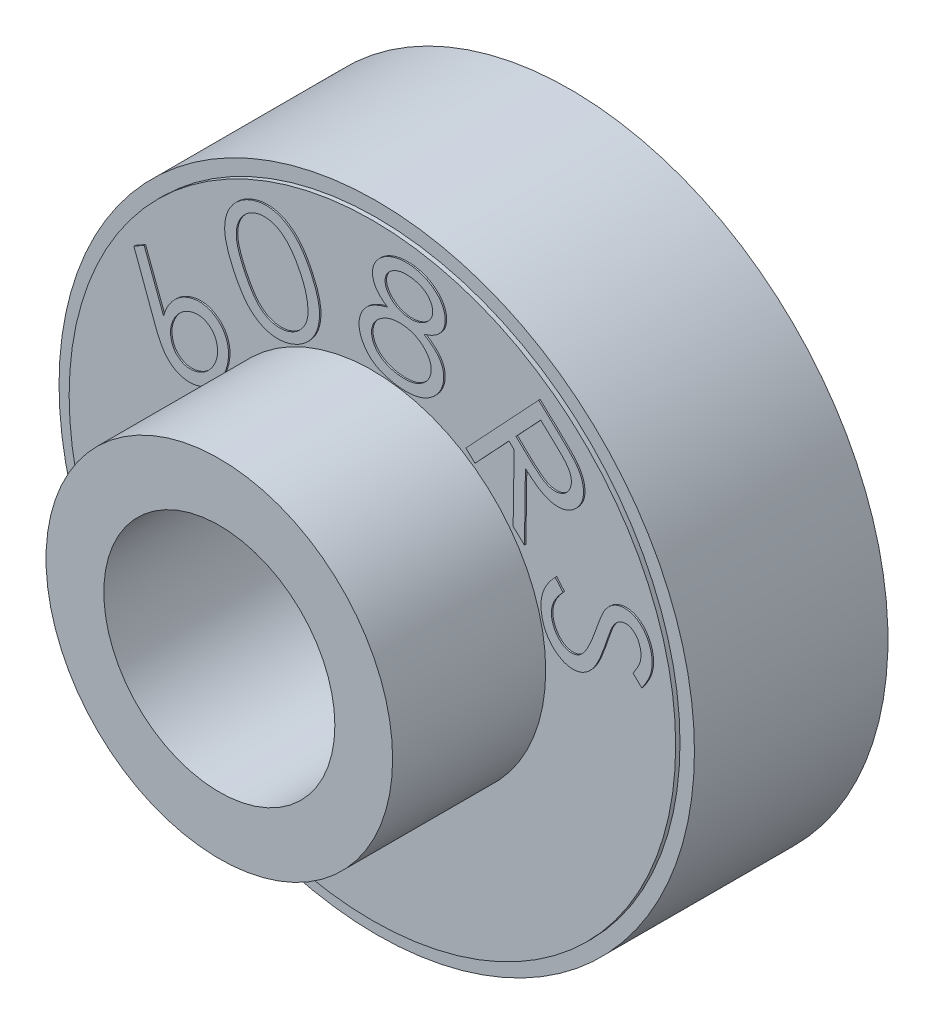
SolidWorks part; units mm, degrees
ref_plane "Front Plane" through (0, 0, 0) normal (0, 0, 1) x (1, 0, 0)
ref_plane "Top Plane" through (0, 0, 0) normal (0, 1, 0) x (1, 0, 0)
ref_plane "Right Plane" through (0, 0, 0) normal (1, 0, 0) x (0, 0, -1)
sketch "Sketch1" plane through (0, 0, 0) normal (0, 0, 1) x (1, 0, 0)
  circle A0 centre (0, 0) radius 11
extrude "Boss-Extrude1" add sketch "Sketch1" along normal blind 7
sketch "Sketch2" plane through (0, 0, 7) normal (0, 0, 1) x (1, 0, 0)
  circle A0 centre (0, 0) radius 4
extrude "Cut-Extrude1" cut sketch "Sketch2" against normal through all
sketch "Sketch3" plane through (0, 0, 7) normal (0, 0, 1) x (1, 0, 0)
  circle A0 centre (0, 0) radius 6
  circle A1 centre (0, 0) radius 4
extrude "Boss-Extrude2" add sketch "Sketch3" along normal blind 5.3
sketch "Sketch4" plane through (0, 0, 7) normal (0, 0, 1) x (1, 0, 0)
  circle A0 centre (0, 0) radius 10.5
  circle A1 centre (0, 0) radius 11
extrude "Cut-Extrude2" cut sketch "Sketch4" against normal blind 0.15
sketch "Sketch5" plane through (0, 0, 0) normal (0, 0, -1) x (-1, 0, 0)
  circle A0 centre (0, 0) radius 21
  circle A1 centre (0, 0) radius 10
extrude "Cut-Extrude3" cut sketch "Sketch5" against normal blind 0.15
sketch "Sketch8" plane through (0, 0, 7) normal (0, 0, 1) x (1, 0, 0)
  circle A0 centre (0, 0) radius 6.4 construction
  text T0 "608RS" font "Century Gothic" height in points 14
extrude "Boss-Extrude3" add sketch "Sketch8" along normal blind 0.05
move or copy body "Body-Move/Copy1" [suppressed] bodies to move or copy 106
